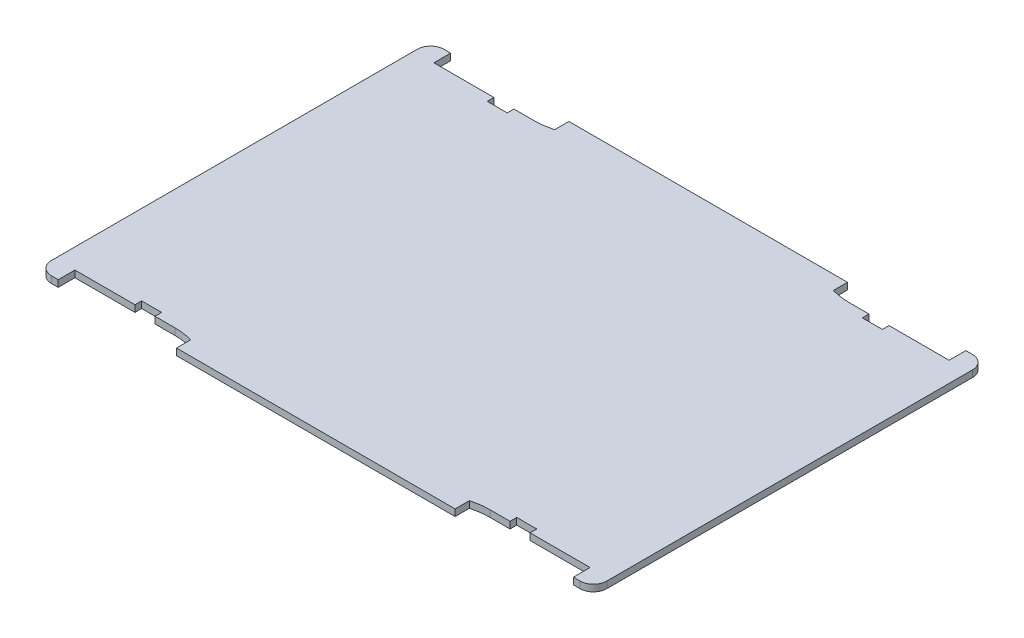
SolidWorks part; units mm, degrees
ref_plane "Alzado" through (0, 0, 0) normal (0, 0, 1) x (1, 0, 0)
ref_plane "Planta" through (0, 0, 0) normal (0, 1, 0) x (1, 0, 0)
ref_plane "Vista lateral" through (0, 0, 0) normal (1, 0, 0) x (0, 0, -1)
sketch "Croquis1" plane through (0, 0, 0) normal (0, 1, 0) x (1, 0, 0)
  line L1 (-208, -147) -> (208, -147)
  line L2 (-208, -147) -> (-208, 147)
  line L3 (-208, 147) -> (208, 147)
  line L4 (208, -147) -> (208, 147)
  line L5 (-208, -147) -> (208, 147) construction
  line L6 (-208, 147) -> (208, -147) construction
  point P0 (0, 0)
  dimension "D1" = 416
  dimension "D2" = 294
extrude "Saliente-Extruir1" add sketch "Croquis1" along normal blind 5
sketch "Croquis2" plane through (0, 5, 0) normal (0, 1, 0) x (1, 0, 0)
  line L0 (-193, 154.4675) -> (-193, 134.4675)
  line L1 (-193, 134.4675) -> (-148, 134.4675)
  line L2 (-148, 134.4675) -> (-148, 129.4675)
  line L3 (-148, 129.4675) -> (-133, 129.4675)
  line L4 (-133, 129.4675) -> (-133, 134.4675)
  line L5 (-133, 134.4675) -> (-118, 134.4675)
  line L6 (-104.374, 136.36) -> (-104.374, 156.36)
  line L7 (-104.374, 156.36) -> (-193.374, 156.36)
  line L8 (-193.374, 156.36) -> (-193, 154.4675)
  line L9 (-208, 147) -> (-208, -147) construction
  line L10 (208, 147) -> (-208, 147) construction
  arc A0 (-118, 134.4675) -> (-104.374, 136.36) centre (-118, 184.4675) ccw
  dimension "D7" = 50
  dimension "D2" = 45
  dimension "D3" = 15
  dimension "D4" = 5
  dimension "D5" = 15
  dimension "D6" = 5
  dimension "D8" = 20
  dimension "D9" = 15
  dimension "D10" = 89
  dimension "D11" = 9.36
  dimension "D12" = 12.5325
extrude "Cortar-Extruir1" cut sketch "Croquis2" against normal through all
mirror "Simetría1" about plane through (0, 0, 0) normal (0, 0, 1) of "Cortar-Extruir1"
mirror "Simetría2" about plane through (0, 0, 0) normal (1, 0, 0) of "Simetría1", "Cortar-Extruir1"
fillet "Redondeo1" radius 10 4 edges at (208, 2.5, -147) (-208, 2.5, -147) (208, 2.5, 147) (-208, 2.5, 147)
